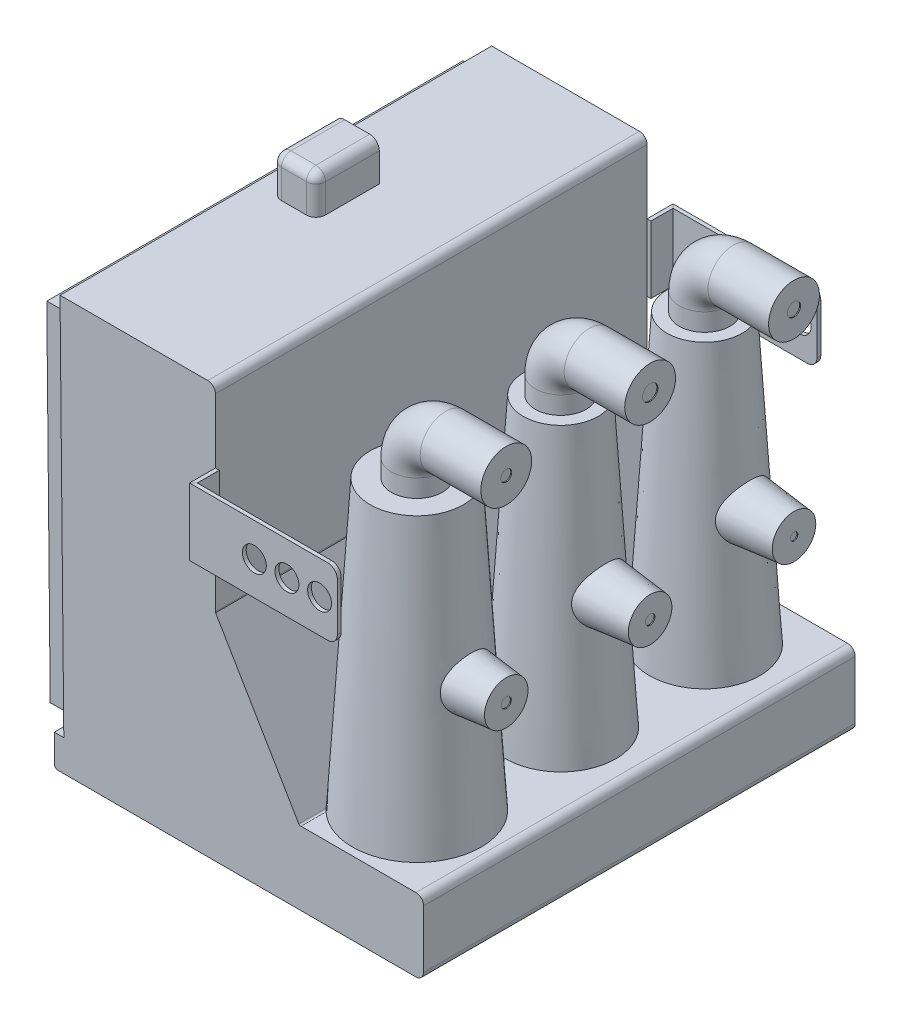
SolidWorks part; units mm, degrees
ref_plane "Alzado" through (0, 0, 0) normal (0, 0, 1) x (1, 0, 0)
ref_plane "Planta" through (0, 0, 0) normal (0, 1, 0) x (1, 0, 0)
ref_plane "Vista lateral" through (0, 0, 0) normal (1, 0, 0) x (0, 0, -1)
sketch "Croquis1" plane through (0, 0, 0) normal (0, 0, 1) x (1, 0, 0)
  line L0 (2.0023, 425.9953) -> (156.0362, 425.9953)
  line L1 (164.0455, 417.986) -> (164.0455, 221.4437)
  line L2 (164.1875, 220.3864) -> (250.9953, 73.02)
  line L3 (253.1611, 72.196) -> (372.986, 72.196)
  line L4 (4.4415, 180.8404) -> (307.4415, 180.8404) construction
  line L5 (380.9953, 64.1866) -> (380.9953, 4.0047)
  line L6 (372.986, -4.0047) -> (0, -4.0047)
  line L7 (-4.0047, 0) -> (-4.0047, 28.5331)
  line L8 (-4.0047, 28.5331) -> (5.9569, 28.5331)
  line L9 (5.9569, 28.5331) -> (2.0023, 425.9953)
  arc A0 (156.0362, 425.9953) -> (164.0455, 417.986) centre (156.0362, 417.986) cw
  arc A1 (164.0455, 221.4437) -> (164.1875, 220.3864) centre (168.0501, 221.4437) ccw
  arc A3 (250.9953, 73.02) -> (253.1611, 72.196) centre (252.5931, 73.9612) ccw
  arc A5 (372.986, 72.196) -> (380.9953, 64.1866) centre (372.986, 64.1866) cw
  arc A7 (380.9953, 4.0047) -> (372.986, -4.0047) centre (372.986, 4.0047) cw
  arc A8 (0, -4.0047) -> (-4.0047, 0) centre (0, 0) cw
  dimension "D1" = 430
  dimension "D2" = 160
  dimension "D3" = 130
  dimension "D4" = 385
  dimension "D5" = 9.9616
  dimension "D6" = 303
extrude "Saliente-Extruir2" add sketch "Croquis1" along normal blind 450
sketch "Croquis3" plane through (0, 72.196, 0) normal (0, 1, 0) x (1, 0, 0)
  line L0 (-4.0047, -225) -> (298.9953, -225) construction
  line L1 (-4.0047, -450) -> (-4.0047, 0) construction
  line L2 (298.9953, -225) -> (298.9953, -375) construction
  line L3 (298.9953, -225) -> (298.9953, -75) construction
  circle A0 centre (298.9953, -375) radius 67
  circle A1 centre (298.9953, -225) radius 57.5
  circle A2 centre (298.9953, -75) radius 57.5
  dimension "D4" = 115
  dimension "D5" = 115
  dimension "D6" = 134
  dimension "D1" = 303
  dimension "D2" = 150
  dimension "D3" = 150
extrude "Saliente-Extruir3" add sketch "Croquis3" along normal blind 300 draft 3.5
sketch "Croquis4" plane through (0, 372.196, 0) normal (0, 1, 0) x (1, 0, 0)
  line L1 (298.9953, -423.6512) -> (298.9953, -35.8488) construction
  circle A3 centre (298.9953, -375) radius 48.6512 construction
  circle A4 centre (298.9953, -75) radius 39.1512 construction
ref_plane "Plano1" through (298.9953, 0, 0) normal (1, 0, 0) x (0, 0, -1)
sketch "Croquis5" plane through (298.9953, 0, 0) normal (1, 0, 0) x (0, 0, -1)
  line L0 (-341.5665, 72.196) -> (-282.5, 72.196) construction
  line L1 (-375, 420.696) -> (-75, 420.696) construction
  line L3 (-282.5, 72.196) -> (-341.5665, 72.196) construction
  line L4 (-225, 215.696) -> (-225, -4.0047) construction
  line L5 (-225, 215.696) -> (-375, 215.696) construction
  line L6 (-375, 215.696) -> (-375, 260.4075) construction
  line L7 (-225, 215.696) -> (-75, 215.696) construction
  line L8 (-75, 215.696) -> (-75, 286.5313) construction
  line L9 (-326.3488, 372.196) -> (-423.6512, 372.196) construction
  line L10 (-423.6512, 372.196) -> (-375, 372.196) construction
  line L11 (-375, 372.196) -> (-375, 215.696) construction
  line L12 (-114.1512, 372.196) -> (-35.8488, 372.196) construction
  line L13 (-35.8488, 372.196) -> (-75, 372.196) construction
  line L14 (-75, 372.196) -> (-75, 215.696) construction
  line L15 (-450, -4.0047) -> (0, -4.0047) construction
  line L17 (-225, 215.696) -> (-225, 420.696) construction
  line L18 (-450, 72.196) -> (-423.8694, 72.196) construction
  circle A0 centre (-225, 215.696) radius 32.5
  circle A1 centre (-375, 215.696) radius 32.5
  circle A2 centre (-75, 215.696) radius 32.5
  circle A3 centre (-225, 420.696) radius 12.5
  circle A4 centre (-375, 420.696) radius 12.5
  circle A5 centre (-75, 420.696) radius 12.5
  dimension "D2" = 65
  dimension "D3" = 65
  dimension "D4" = 65
  dimension "D5" = 25
  dimension "D6" = 25
  dimension "D7" = 25
  dimension "D8" = 348.5
  dimension "D9" = 205
extrude "Saliente-Extruir6" add sketch "Croquis5" along normal blind 93.19 draft 6
sketch "Croquis7" plane through (6.2402, 0.0621, 0) normal (-1, -0.0099, 0) x (0, 0, 1)
  line L0 (450, 425.9543) -> (0, 425.9543) construction
  line L1 (8, 45.0745) -> (442, 45.0745)
  line L2 (8, 45.0745) -> (8, 405.9543)
  line L3 (8, 405.9543) -> (442, 405.9543)
  line L4 (442, 45.0745) -> (442, 405.9543)
  line L5 (8, 45.0745) -> (442, 405.9543) construction
  line L6 (8, 405.9543) -> (442, 45.0745) construction
  line L7 (450, 425.9543) -> (450, 28.4725) construction
  line L8 (0, 425.9543) -> (0, 28.4725) construction
  point P0 (225, 225.5144)
  dimension "D1" = 20
  dimension "D2" = 8
  dimension "D3" = 8
extrude "Saliente-Extruir7" add sketch "Croquis7" along normal blind 22
sketch "Croquis8" plane through (0, 372.196, 0) normal (0, 1, 0) x (1, 0, 0)
  line L0 (298.9953, -375) -> (395.9362, -375) construction
  line L1 (259.8441, -225) -> (392.1853, -225) construction
  line L2 (392.1853, -227.7053) -> (392.1853, -222.2947) construction
  line L3 (259.8441, -75) -> (388.9953, -75) construction
  circle A0 centre (298.9953, -225) radius 39.1512 construction
  circle A1 centre (298.9953, -75) radius 39.1512 construction
ref_plane "Plano2" through (0, 0, 375) normal (0, 0, 1) x (1, 0, 0)
ref_plane "Plano3" through (0, 0, 225) normal (0, 0, 1) x (1, 0, 0)
ref_plane "Plano4" through (0, 0, 75) normal (0, 0, 1) x (1, 0, 0)
sketch "Croquis9" plane through (0, 425.9953, 0) normal (0, 1, 0) x (1, 0, 0)
  line L0 (2.0023, -225) -> (22.0023, -225) construction
  line L1 (2.0023, -450) -> (2.0023, 0) construction
  line L4 (68.0023, -183.1696) -> (22.0023, -183.1696)
  line L5 (68.0023, -183.1696) -> (68.0023, -249.1696)
  line L6 (68.0023, -249.1696) -> (22.0023, -249.1696)
  line L7 (22.0023, -183.1696) -> (22.0023, -249.1696)
  line L8 (68.0023, -183.1696) -> (22.0023, -249.1696) construction
  line L9 (68.0023, -249.1696) -> (22.0023, -183.1696) construction
  point P6 (45.0023, -216.1696)
  dimension "D1" = 20
  dimension "D2" = 46
  dimension "D3" = 66
extrude "Saliente-Extruir8" add sketch "Croquis9" along normal blind 40
fillet "Redondeo1" radius 10 5 edges at (22.0023, 465.9953, 216.1696) (22.0023, 445.9953, 249.1696) (45.0023, 465.9953, 249.1696) (68.0023, 445.9953, 249.1696) (68.0023, 465.9953, 216.1696)
sketch "Croquis10" plane through (0, 0, 450) normal (0, 0, 1) x (1, 0, 0)
  line L0 (156.0362, 425.9953) -> (2.0023, 425.9953) construction
  line L1 (164.0455, 280.9953) -> (168.0455, 280.9953)
  line L2 (164.0455, 280.9953) -> (164.0455, 350.9953)
  line L3 (164.0455, 350.9953) -> (168.0455, 350.9953)
  line L4 (168.0455, 280.9953) -> (168.0455, 350.9953)
  line L5 (164.0455, 280.9953) -> (168.0455, 350.9953) construction
  line L6 (164.0455, 350.9953) -> (168.0455, 280.9953) construction
  line L8 (164.0455, 221.4437) -> (164.0455, 417.986) construction
  point P0 (166.0455, 315.9953)
  dimension "D1" = 4
  dimension "D2" = 70
  dimension "D3" = 75
sketch3d "Croquis3D1"
  line L0 (166.0455, 315.9953, 450) -> (166.0455, 315.9953, 475)
  line L1 (166.0455, 315.9953, 475) -> (218.0943, 315.9953, 475)
  dimension "D1" = 25
sweep "Barrer1" add profiles "Croquis10" path "Croquis3D1"
mirror "Simetría2" about plane through (0, 0, 225) normal (0, 0, 1) of "Barrer1"
sketch "Croquis11" plane through (0, 0, 0) normal (0, 0, -1) x (-1, 0, 0)
  line L0 (-164.0455, 350.9953) -> (-168.0455, 350.9953)
  line L1 (-168.0455, 350.9953) -> (-168.0455, 280.9953)
  line L2 (-168.0455, 280.9953) -> (-164.0455, 280.9953)
  line L3 (-164.0455, 280.9953) -> (-164.0455, 350.9953)
  line L4 (-168.0455, 350.9953) -> (-164.0455, 280.9953) construction
  line L5 (-164.0455, 350.9953) -> (-168.0455, 280.9953) construction
sketch3d "Croquis3D3"
  line L0 (166.0455, 315.9953, 0) -> (166.0455, 315.9953, -25)
  line L1 (168.0455, 350.9953, 0) -> (164.0455, 280.9953, 0) construction
  line L2 (166.0455, 315.9953, -25) -> (218.1367, 315.9953, -25)
  dimension "D1" = 25
sweep "Barrer2" add profiles "Croquis11" path "Croquis3D3"
ref_plane "Plano5" through (0, 242.196, 0) normal (0, 1, 0) x (1, 0, 0)
sketch "Croquis15" plane through (0, 72.196, 0) normal (0, 1, 0) x (1, 0, 0)
  line L0 (298.9953, -423.6512) -> (298.9953, -35.8488) construction
  line L1 (259.8441, -75) -> (388.9953, -75) construction
  circle A0 centre (298.9953, -375) radius 26.5
  circle A1 centre (298.9953, -225) radius 26.5
  circle A2 centre (298.9953, -75) radius 26.5
  dimension "D1" = 53
  dimension "D2" = 53
  dimension "D3" = 53
sketch3d "Croquis3D5"
  line L0 (298.9953, 72.196, 375) -> (298.9953, 341.4336, 375)
  line L1 (298.9953, 372.196, 375) -> (395.9362, 372.196, 375) construction
  line L2 (392.1853, 420.696, 375) -> (328.9953, 420.696, 375)
  line L3 (298.9953, 420.696, 375) -> (392.1853, 420.696, 375) construction
  line L4 (298.9953, 390.696, 375) -> (298.9953, 341.4336, 375)
  arc A0 (298.9953, 390.696, 375) -> (328.9953, 420.696, 375) centre (328.9953, 390.696, 375) ccw
  point P8 (298.9953, 372.196, 375)
  point P12 (298.9953, 420.696, 375)
  point P13 (328.9953, 390.696, 345)
  dimension "D1" = 30
sweep "Barrer7" add profiles "Croquis15" path "Croquis3D5"
ref_plane "Plano6" through (0, 0, 225) normal (0, 0, 1) x (1, 0, 0)
sketch "Croquis16" plane through (392.1853, 0, 0) normal (1, 0, 0) x (0, 0, -1)
  circle A0 centre (-375, 420.696) radius 5.7549
  circle A1 centre (-225, 420.696) radius 8.0609
  circle A2 centre (-75, 420.696) radius 6.9295
  circle A3 centre (-375, 215.696) radius 5.2681
  circle A4 centre (-225, 215.696) radius 5.036
  circle A5 centre (-75, 215.696) radius 3.9655
extrude "Cortar-Extruir1" cut sketch "Croquis16" against normal blind 1
sketch "Croquis17" plane through (218.0943, 0, 0) normal (1, 0, 0) x (0, 0, -1)
  line L0 (-477, 350.9953) -> (-473, 350.9953)
  line L1 (-473, 350.9953) -> (-473, 280.9953)
  line L2 (-473, 280.9953) -> (-473, 350.9953) construction
  line L3 (-450, 280.9953) -> (-473, 280.9953) construction
  line L4 (-473, 280.9953) -> (-477, 280.9953)
  line L5 (-477, 280.9953) -> (-477, 350.9953)
extrude "Saliente-Extruir9" add sketch "Croquis17" along normal blind 100
sketch "Croquis18" plane through (0, 0, 477) normal (0, 0, 1) x (1, 0, 0)
  line L0 (318.0943, 315.9953) -> (164.0455, 315.9953) construction
  line L1 (318.0943, 350.9953) -> (318.0943, 280.9953) construction
  line L2 (164.0455, 280.9953) -> (164.0455, 350.9953) construction
  line L3 (312.0943, 315.9953) -> (312.0943, 322.6968) construction
  line L4 (278.0943, 315.9953) -> (278.0943, 302.6341) construction
  line L5 (244.0943, 315.9953) -> (241.1844, 271.9911) construction
  line L6 (253.0943, 315.9953) -> (253.0943, 306.1303) construction
  line L7 (287.0943, 315.9953) -> (287.0943, 306.1303) construction
  circle A0 centre (231.5943, 315.9953) radius 12.5
  circle A1 centre (265.5943, 315.9953) radius 12.5
  circle A2 centre (299.5943, 315.9953) radius 12.5
  dimension "D1" = 25
  dimension "D2" = 25
  dimension "D3" = 25
  dimension "D4" = 6
  dimension "D5" = 9
  dimension "D6" = 9
extrude "Cortar-Extruir2" cut sketch "Croquis18" against normal blind 5
sketch "Croquis19" plane through (218.1367, 0, 0) normal (1, 0, 0) x (0, 0, -1)
  line L0 (23, 350.9953) -> (27, 350.9953)
  line L1 (27, 350.9953) -> (27, 280.9953)
  line L2 (27, 280.9953) -> (23, 280.9953)
  line L3 (23, 280.9953) -> (23, 350.9953)
extrude "Saliente-Extruir10" add sketch "Croquis19" along normal up to surface (99.9576 mm away) up to face at (318.0943, 315.9953, 475)
sketch "Croquis20" plane through (0, 0, -23) normal (0, 0, 1) x (1, 0, 0)
  circle A0 centre (231.5943, 315.9953) radius 12.5
  circle A1 centre (265.5943, 315.9953) radius 12.5
  circle A2 centre (299.5943, 315.9953) radius 12.5
extrude "Cortar-Extruir3" cut sketch "Croquis20" against normal blind 10
fillet "Redondeo2" radius 10 2 edges at (318.0943, 280.9953, 475) (318.0943, 350.9953, 475)
fillet "Redondeo3" radius 10 2 edges at (318.0943, 280.9953, -25) (318.0943, 350.9953, -25)
